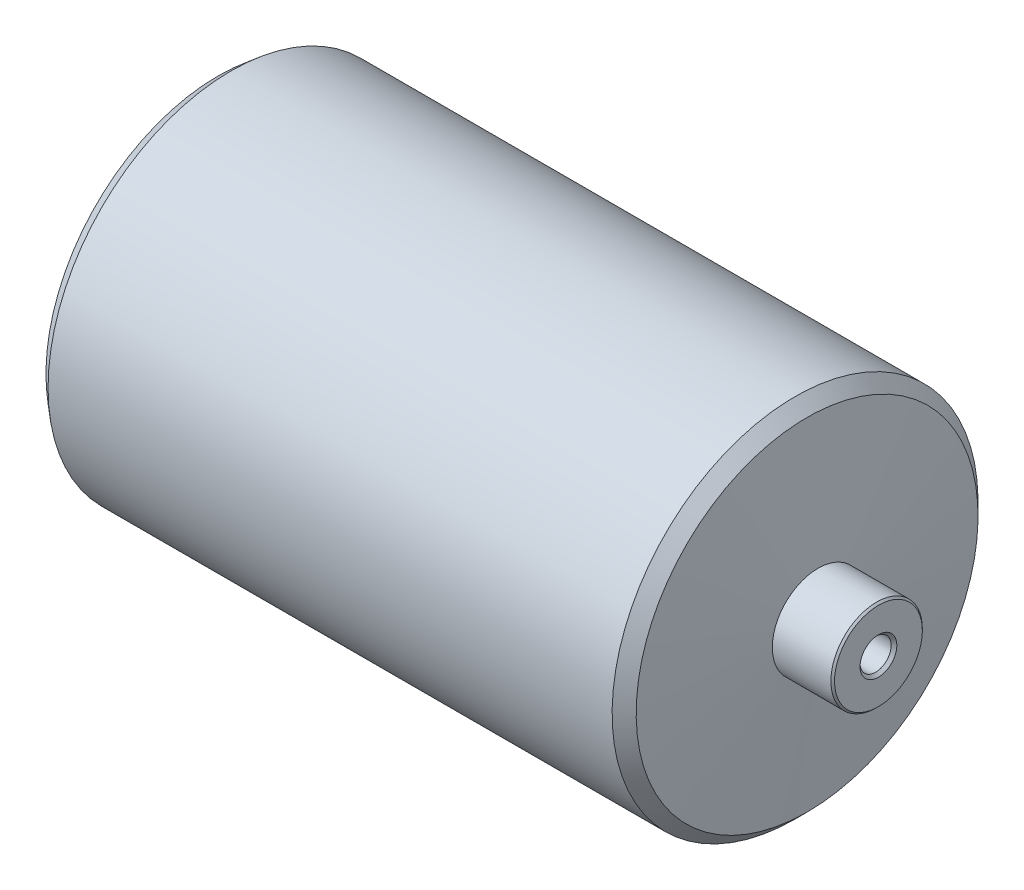
SolidWorks part; units mm, degrees
ref_plane "Front Plane" through (0, 0, 0) normal (0, 0, 1) x (1, 0, 0)
ref_plane "Top Plane" through (0, 0, 0) normal (0, 1, 0) x (1, 0, 0)
ref_plane "Right Plane" through (0, 0, 0) normal (1, 0, 0) x (0, 0, -1)
sketch "Sketch1" plane through (0, 0, 0) normal (0, 0, 1) x (1, 0, 0)
  line L0 (-100, 0) -> (-100, 12.5)
  line L1 (-100, 12.5) -> (-83.5, 12.5)
  line L5 (83.5, 12.5) -> (100, 12.5)
  line L6 (100, 12.5) -> (100, 0)
  line L7 (100, 0) -> (-100, 0)
  line L8 (-83.5, 12.5) -> (-80.2192, 50)
  line L9 (-80.2192, 50) -> (80.2192, 50)
  line L10 (80.2192, 50) -> (83.5, 12.5)
  point P2 (0, 0)
  point P5 (0, 50)
  point P11 (100, 6.25)
  dimension "D1" = 95
  dimension "D2" = 16.5
  dimension "D3" = 50
  dimension "D4" = 200
  dimension "D5" = 95
  dimension "D6" = 12.5
revolve "Revolve1" add sketch "Sketch1" angle 360 about L7
chamfer "Chamfer1" distance 0.5 angle 45 1 edges at (-100, 12.5, 0)
chamfer "Chamfer2" distance 3 angle 45 1 edges at (-80.2192, 50, 0)
chamfer "Chamfer3" distance 3 angle 45 1 edges at (80.2192, 50, 0)
chamfer "Chamfer4" distance 0.5 angle 45 1 edges at (100, 12.5, 0)
sketch "Sketch2" plane through (100, 0, 0) normal (1, 0, 0) x (0, 0, -1)
  circle A0 centre (0, 0) radius 5
  dimension "D1" = 10
hole_wizard "M10 Tapped Hole1" positions "3DSketch1" profile "Sketch5" tap size "M10" standard "ISO"
sketch3d "3DSketch1"
  circle A0 centre (-99.5, 0, 0) radius 12.5 construction
  point P0 (100, 0, 0)
  point P3 (-99.5, 0, 0)
  point P7 (-87, 0, 0)
  point P9 (0, 0, 0)
sketch "Sketch5" plane through (100, 0, 0) normal (0, 1, 0) x (0, 0, -1)
  line L0 (0, 0) -> (0, 59)
  line L1 (0, 59) -> (4.25, 56.4463)
  line L2 (4.25, 56.4463) -> (4.25, 0.775)
  line L3 (4.25, 0.775) -> (5.025, 0)
  line L5 (5.025, 0) -> (0, 0)
  line L6 (-4.25, 0.775) -> (-5.025, 0) construction
  line L10 (0, 59) -> (-4.25, 56.4463) construction
  line L11 (0, -6.35) -> (0, 107.95) construction
  dimension "Tap Drill Dia." = 8.5
  dimension "Tap Drill Depth" = 59
  dimension "Near C'Sink Dia." = 10.05
  dimension "Near C'Sink Angle" = 90
  dimension "Drill Angle" = 118
cosmetic thread "Hole Thread1" parameters "D1"=20, "D2"=10
cosmetic thread "Hole Thread2" parameters "D1"=20, "D2"=10
sketch "Sketch7" plane through (-100, 0, 0) normal (-1, 0, 0) x (0, 0, 1)
  point P0 (0, 0)
hole_wizard "M10 Tapped Hole2" positions "3DSketch3" profile "Sketch8" tap size "M10" standard "ISO"
sketch3d "3DSketch3"
  point P0 (-100, 0, 0)
sketch "Sketch8" plane through (-100, 0, 0) normal (0, 1, 0) x (0, 0, 1)
  line L0 (0, 0) -> (0, 59)
  line L1 (0, 59) -> (4.25, 56.4463)
  line L2 (4.25, 56.4463) -> (4.25, 0.775)
  line L3 (4.25, 0.775) -> (5.025, 0)
  line L5 (5.025, 0) -> (0, 0)
  line L6 (-4.25, 0.775) -> (-5.025, 0) construction
  line L10 (0, 59) -> (-4.25, 56.4463) construction
  line L11 (0, -6.35) -> (0, 107.95) construction
  dimension "Tap Drill Dia." = 8.5
  dimension "Tap Drill Depth" = 59
  dimension "Near C'Sink Dia." = 10.05
  dimension "Near C'Sink Angle" = 90
  dimension "Drill Angle" = 118
cosmetic thread "Hole Thread3" parameters "D1"=20, "D2"=10
